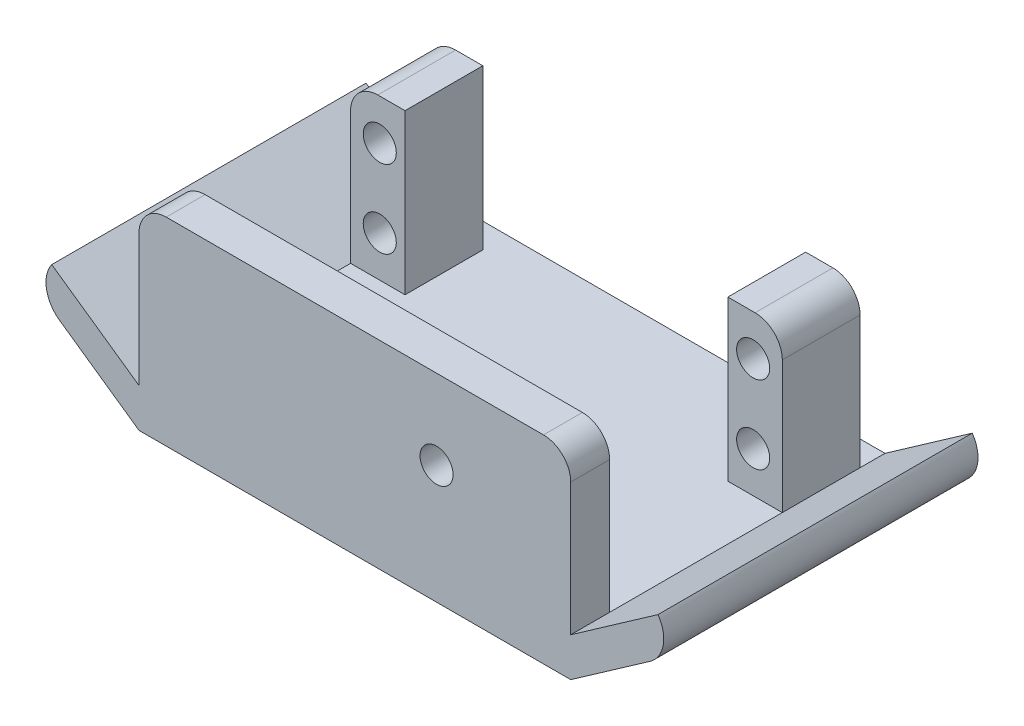
SolidWorks part; units mm, degrees
ref_plane "Front" through (0, 0, 0) normal (0, 0, 1) x (1, 0, 0)
ref_plane "Top" through (0, 0, 0) normal (0, 1, 0) x (1, 0, 0)
ref_plane "Right" through (0, 0, 0) normal (1, 0, 0) x (0, 0, -1)
sketch "Sketch1" plane through (0, 0, 0) normal (0, 1, 0) x (1, 0, 0)
  line L1 (0, 0) -> (55.5, 0)
  line L2 (0, 0) -> (0, 40.4)
  line L3 (0, 40.4) -> (55.5, 40.4)
  line L4 (55.5, 0) -> (55.5, 40.4)
  dimension "D1" = 55.5
  dimension "D2" = 40.4
extrude "base" add sketch "Sketch1" along normal blind 5
sketch "Sketch2" plane through (0, 0, -40.4) normal (0, 0, -1) x (-1, 0, 0)
  line L1 (0, 5) -> (0, 0) construction
  line L2 (-55.5, 0) -> (0, 0)
  line L3 (-55.5, 0) -> (-55.5, 25.5)
  line L4 (-55.5, 25.5) -> (0, 25.5)
  line L5 (0, 0) -> (0, 25.5)
  line L6 (-55.5, 5) -> (0, 5) construction
  dimension "D1" = 20.5
extrude "wall" add sketch "Sketch2" against normal blind 5
ref_plane "Plane1" through (0, 0, -8.2) normal (0, 0, 1) x (1, 0, 0)
sketch "Sketch3" plane through (0, 0, -8.2) normal (0, 0, 1) x (1, 0, 0)
  line L0 (0, 5) -> (55.5, 5) construction
  line L1 (0, 25.5) -> (7, 25.5)
  line L2 (0, 25.5) -> (0, 5)
  line L3 (0, 5) -> (7, 5)
  line L4 (7, 25.5) -> (7, 5)
  line L5 (27.75, 5) -> (27.75, 25.5) construction
  line L6 (55.5, 5) -> (0, 5) construction
  line L7 (0, 25.5) -> (55.5, 25.5) construction
  line L8 (55.5, 5) -> (48.5, 5)
  line L9 (48.5, 25.5) -> (48.5, 5)
  line L10 (55.5, 25.5) -> (48.5, 25.5)
  line L11 (55.5, 25.5) -> (55.5, 5)
  dimension "D1" = 7
extrude "mountingTabs" add sketch "Sketch3" along normal blind 5
sketch "Sketch4" plane through (0, 0, 0) normal (0, 0, 1) x (1, 0, 0)
  line L0 (27.75, 0) -> (27.75, 25.5) construction
  line L1 (0, 0) -> (55.5, 0) construction
  line L2 (0, 25.5) -> (55.5, 25.5) construction
  line L3 (0, 0) -> (-10.2089, 7.1483)
  line L4 (0, 5) -> (-11.2182, 12.8551)
  line L5 (0, 5) -> (0, 0)
  line L6 (55.5, 5) -> (66.7182, 12.8551)
  line L7 (55.5, 5) -> (55.5, 0)
  line L8 (55.5, 0) -> (65.7089, 7.1483)
  arc A0 (-11.2182, 12.8551) -> (-10.2089, 7.1483) centre (-7.8572, 10.5069) ccw
  arc A1 (66.7182, 12.8551) -> (65.7089, 7.1483) centre (63.3572, 10.5069) cw
  dimension "D1" = 145
  dimension "D2" = 12.4627
  dimension "D3" = 13.6949
extrude "lips" add sketch "Sketch4" against normal up to surface (40.4 mm away) up to face at (27.75, 12.75, -40.4)
sketch "Sketch5" plane through (0, 0, -3.2) normal (0, 0, 1) x (1, 0, 0)
  line L0 (27.75, 0) -> (27.75, 25.5) construction
  line L3 (0, 15.25) -> (55.5, 15.25) construction
  line L4 (0, 25.5) -> (0, 5) construction
  line L5 (55.5, 5) -> (55.5, 25.5) construction
  line L6 (7, 25.5) -> (0, 25.5) construction
  line L7 (0, 0) -> (55.5, 0) construction
  line L8 (0, 25.5) -> (55.5, 25.5) construction
  circle A0 centre (3.75, 20.25) radius 2.125
  circle A1 centre (3.75, 10.25) radius 2.125
  circle A4 centre (51.75, 10.25) radius 2.125
  circle A5 centre (51.75, 20.25) radius 2.125
  dimension "D1" = 4.25
  dimension "D2" = 5.25
  dimension "D3" = 3.75
extrude "mountingHoles" cut sketch "Sketch5" against normal blind 5
fillet "fillets" radius 3.5 4 edges at (55.5, 25.5, -37.9) (55.5, 25.5, -5.7) (0, 25.5, -37.9) (0, 25.5, -5.7)
sketch "Sketch6" plane through (0, 0, -35.4) normal (0, 0, 1) x (1, 0, 0)
  line L0 (3.5, 25.5) -> (52, 25.5) construction
  line L1 (55.5, 5) -> (55.5, 22) construction
  circle A0 centre (38.25, 15.25) radius 2.125
  dimension "D1" = 4.25
  dimension "D2" = 10.25
  dimension "D3" = 17.25
extrude "throughHole" cut sketch "Sketch6" against normal blind 5
ref_plane "Plane2" through (0, 0, 0) normal (0, 0, 1) x (1, 0, 0)
mirror "Mirror3" about plane through (0, 0, 0) normal (0, 0, 1) of "fillets", "throughHole", "mountingHoles", "lips", "mountingTabs", "wall", "base"
sketch "Sketch7" plane through (0, 0, 0) normal (0, 0, 1) x (1, 0, 0)
  line L1 (-26.7687, 48.7867) -> (77.7481, 48.7867)
  line L2 (-26.7687, 48.7867) -> (-26.7687, -17.5413)
  line L3 (-26.7687, -17.5413) -> (77.7481, -17.5413)
  line L4 (77.7481, 48.7867) -> (77.7481, -17.5413)
extrude "Cut-Extrude1" cut sketch "Sketch7" against normal blind 73
sketch "Sketch8" plane through (0, 0, 8.2) normal (0, 0, 1) x (1, 0, 0)
  line L4 (7, 25.5) -> (3.5, 25.5)
  line L5 (0, 22) -> (0, 5)
  line L6 (0, 5) -> (7, 5)
  line L7 (7, 5) -> (7, 25.5)
  line L8 (7, 25.5) -> (3.5, 25.5)
  line L9 (0, 22) -> (0, 5)
  line L10 (0, 5) -> (7, 5)
  line L11 (7, 5) -> (7, 25.5)
  line L12 (55.5, 5) -> (55.5, 22)
  line L13 (52, 25.5) -> (48.5, 25.5)
  line L14 (48.5, 25.5) -> (48.5, 5)
  line L15 (48.5, 5) -> (55.5, 5)
  line L16 (55.5, 5) -> (55.5, 22)
  line L17 (52, 25.5) -> (48.5, 25.5)
  line L18 (48.5, 25.5) -> (48.5, 5)
  line L19 (48.5, 5) -> (55.5, 5)
  circle A0 centre (3.75, 20.25) radius 2.125 construction
  arc A1 (3.5, 25.5) -> (0, 22) centre (3.5, 22) ccw
  arc A2 (3.5, 25.5) -> (0, 22) centre (3.5, 22) ccw
  arc A3 (55.5, 22) -> (52, 25.5) centre (52, 22) ccw
  arc A4 (55.5, 22) -> (52, 25.5) centre (52, 22) ccw
  circle A5 centre (3.75, 20.25) radius 2.125
  circle A6 centre (3.75, 10.25) radius 2.125 construction
  circle A7 centre (3.75, 10.25) radius 2.125
  circle A8 centre (51.75, 20.25) radius 2.125 construction
  circle A9 centre (51.75, 20.25) radius 2.125
  circle A10 centre (51.75, 10.25) radius 2.125 construction
  circle A11 centre (51.75, 10.25) radius 2.125
  dimension "D1" = 0
  dimension "D2" = 0
extrude "Boss-Extrude1" add sketch "Sketch8" along normal blind 5
